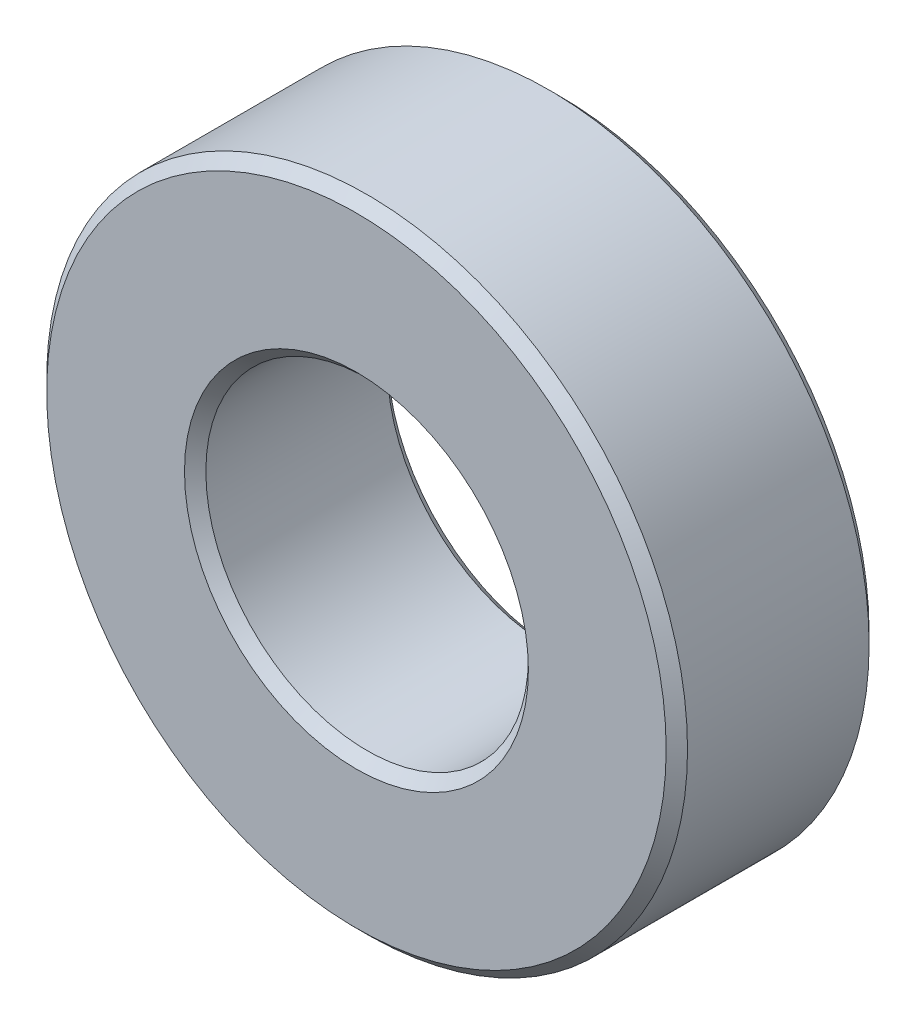
SolidWorks part; units mm, degrees
ref_plane "前视基准面" through (0, 0, 0) normal (0, 0, 1) x (1, 0, 0)
ref_plane "上视基准面" through (0, 0, 0) normal (0, 1, 0) x (1, 0, 0)
ref_plane "右视基准面" through (0, 0, 0) normal (1, 0, 0) x (0, 0, -1)
other "Configuration Table"
sketch "草图1" plane through (0, 0, 0) normal (0, 0, 1) x (1, 0, 0)
  circle A0 centre (0, 0) radius 30
  circle A1 centre (0, 0) radius 15.1
  dimension "D1" = 30.2
  dimension "D2" = 60
extrude "凸台-拉伸1" add sketch "草图1" along normal blind 19
chamfer "倒角1" distance 1 angle 45 4 edges at (15.1, 0, 0) (15.1, 0, 19) (30, 0, 0) (30, 0, 19)
